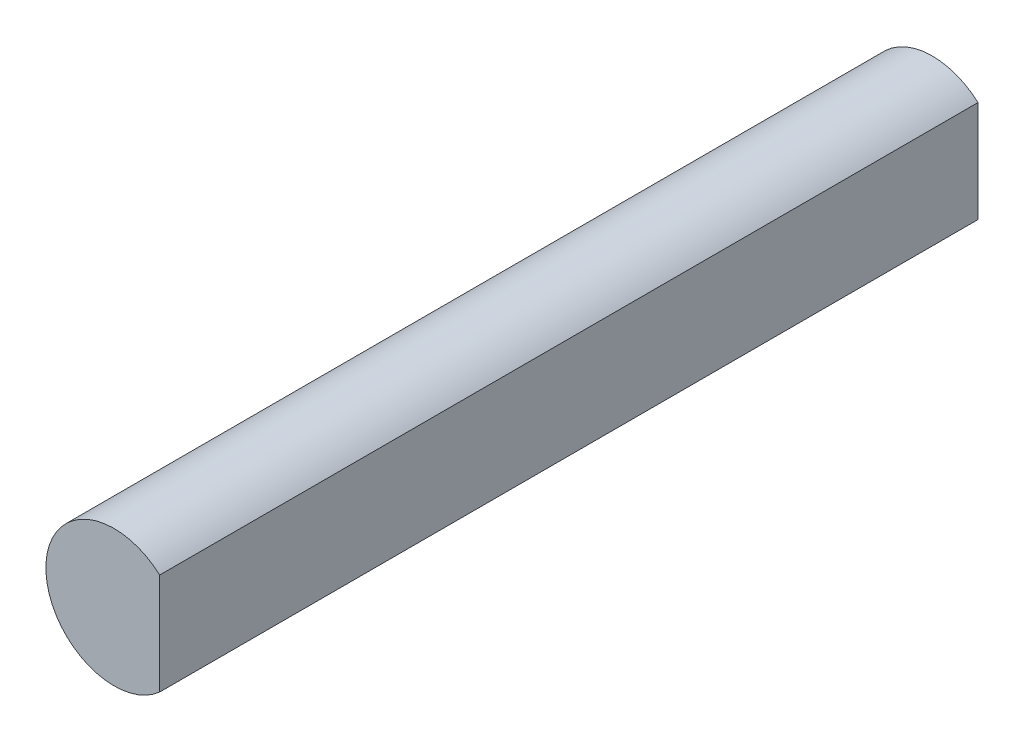
SolidWorks part; units mm, degrees
ref_plane "Alzado" through (0, 0, 0) normal (0, 0, 1) x (1, 0, 0)
ref_plane "Planta" through (0, 0, 0) normal (0, 1, 0) x (1, 0, 0)
ref_plane "Vista lateral" through (0, 0, 0) normal (1, 0, 0) x (0, 0, -1)
sketch "Croquis1" plane through (0, 0, 0) normal (0, 0, 1) x (1, 0, 0)
  circle A0 centre (0, 0) radius 2.5
  dimension "D1" = 5
extrude "Saliente-Extruir1" add sketch "Croquis1" along normal blind 30
sketch "Croquis2" plane through (0, 0, 0) normal (0, 0, -1) x (-1, 0, 0)
  line L0 (-1.6729, 1.8578) -> (-1.6729, -1.8578)
  arc A0 (-1.6729, 1.8578) -> (-1.6729, -1.8578) centre (0, 0) ccw
extrude "Cortar-Extruir1" cut sketch "Croquis2" against normal through all
